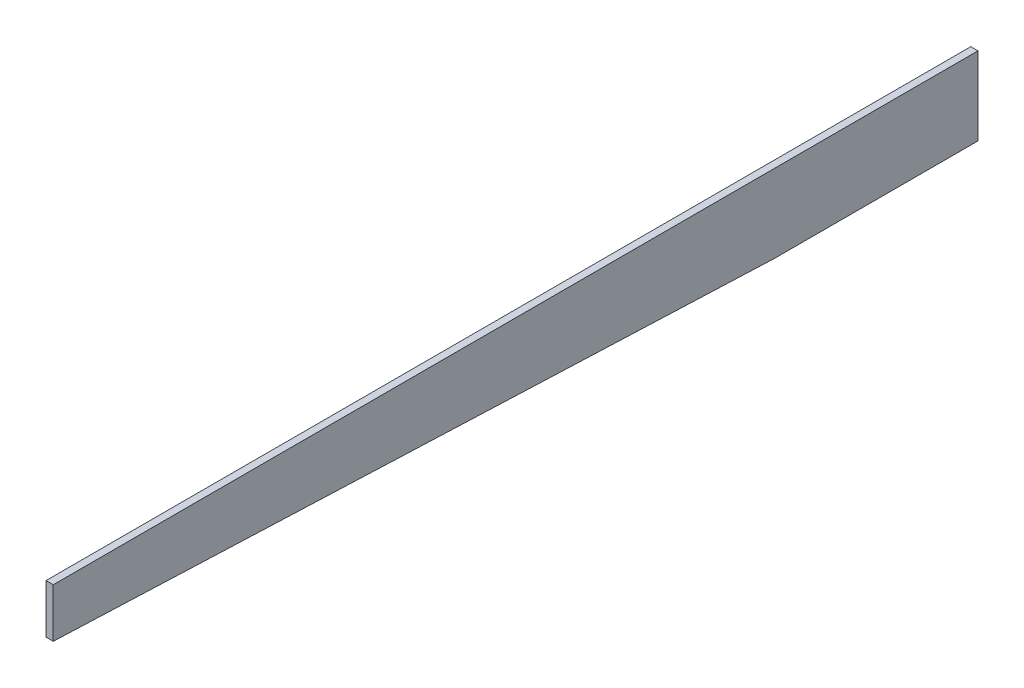
SolidWorks part; units mm, degrees
ref_plane "Front Plane" through (0, 0, 0) normal (0, 0, 1) x (1, 0, 0)
ref_plane "Top Plane" through (0, 0, 0) normal (0, 1, 0) x (1, 0, 0)
ref_plane "Right Plane" through (0, 0, 0) normal (1, 0, 0) x (0, 0, -1)
sketch "Sketch1" plane through (0, 0, 0) normal (1, 0, 0) x (0, 0, -1)
  line L0 (-383, 12.0163) -> (-84.3, 0)
  line L1 (-84.3, 0) -> (0, 0)
  line L2 (0, 0) -> (0, 32.31)
  line L3 (0, 32.31) -> (-383, 32.31)
  line L4 (-390.3, 32.31) -> (-390.3, 12.31) construction
  line L5 (-383, 32.31) -> (-383, 12.0163)
  line L6 (0, 55) -> (0, -55) construction
  line L7 (-390.3, 12.31) -> (-383, 12.0163) construction
  line L8 (-383, 32.31) -> (-390.3, 32.31) construction
  dimension "D1" = 20
  dimension "D2" = 32.31
  dimension "D3" = 84.3
  dimension "D4" = 177.696
  dimension "D5" = 390.3
  dimension "D6" = 383
extrude "Boss-Extrude1" add sketch "Sketch1" along normal blind 3
